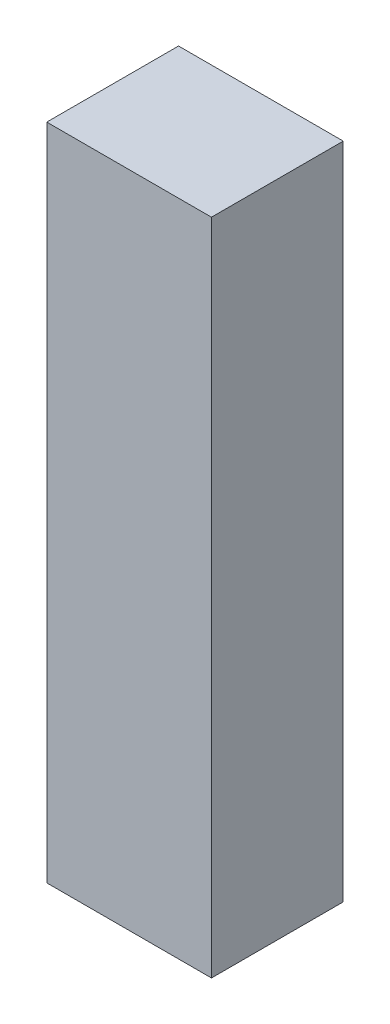
SolidWorks part; units mm, degrees
ref_plane "Front Plane" through (0, 0, 0) normal (0, 0, 1) x (1, 0, 0)
ref_plane "Top Plane" through (0, 0, 0) normal (0, 1, 0) x (1, 0, 0)
ref_plane "Right Plane" through (0, 0, 0) normal (1, 0, 0) x (0, 0, -1)
other "Configuration Table"
sketch "Sketch1" plane through (0, 0, 0) normal (0, 0, 1) x (1, 0, 0)
  line L1 (280, 330) -> (330, 330)
  line L2 (280, 330) -> (280, 530)
  line L3 (280, 530) -> (330, 530)
  line L4 (330, 330) -> (330, 530)
extrude "TOPPING_arka_duvar_pano_surucu_3_1" add sketch "Sketch1" against normal blind 40 from offset 736 separate body
